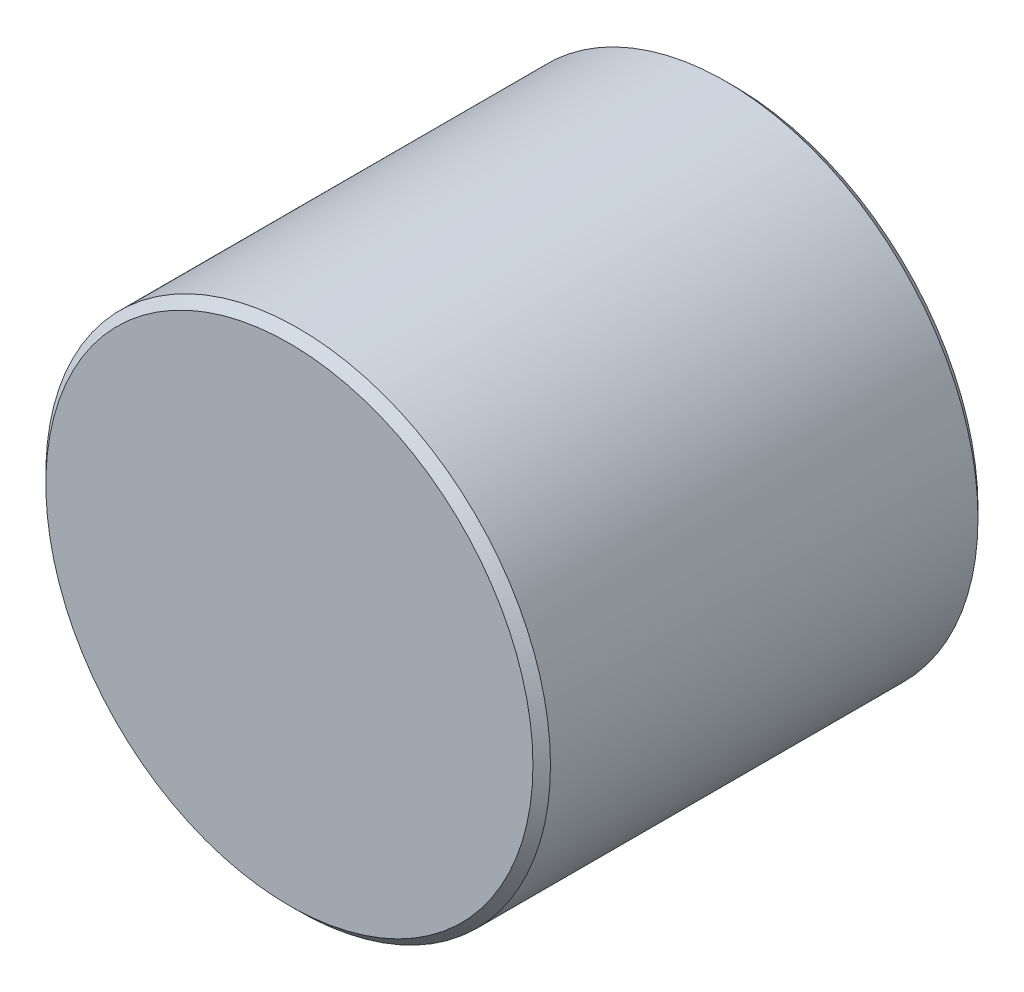
SolidWorks part; units mm, degrees
other "Defeature"
material "6061 Alloy"
ref_plane "Front Plane" through (0, 0, 0) normal (0, 0, 1) x (1, 0, 0)
ref_plane "Top Plane" through (0, 0, 0) normal (0, 1, 0) x (1, 0, 0)
ref_plane "Right Plane" through (0, 0, 0) normal (1, 0, 0) x (0, 0, -1)
sketch "Sketch1" plane through (0, 0, 0) normal (0, 0, 1) x (1, 0, 0)
  circle A0 centre (0, 0) radius 7.2
  dimension "D1" = 14.4
extrude "Boss-Extrude1" add sketch "Sketch1" along normal mid plane 12.7
chamfer "Chamfer1" distance 0.25 angle 45 2 edges at (7.2, 0, -6.35) (7.2, 0, 6.35)
